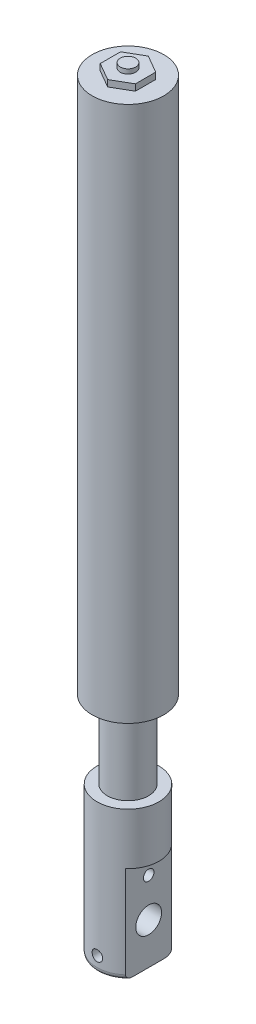
SolidWorks part; units mm, degrees
ref_plane "Piano frontale" through (0, 0, 0) normal (0, 0, 1) x (1, 0, 0)
ref_plane "Piano superiore" through (0, 0, 0) normal (0, 1, 0) x (1, 0, 0)
ref_plane "Piano destro" through (0, 0, 0) normal (1, 0, 0) x (0, 0, -1)
sketch "Schizzo1" plane through (0, 0, 0) normal (0, 1, 0) x (1, 0, 0)
  circle A0 centre (0, 0) radius 6.93
  dimension "D1" = 13.86
extrude "Estrusione-Estrusione1" add sketch "Schizzo1" along normal blind 103.85
sketch "Schizzo2" plane through (0, 103.85, 0) normal (0, 1, 0) x (1, 0, 0)
  line L1 (-3.4078, 1.9675) -> (-3.4078, -1.9675)
  line L2 (-3.4078, -1.9675) -> (0, -3.935)
  line L3 (0, -3.935) -> (3.4078, -1.9675)
  line L4 (3.4078, -1.9675) -> (3.4078, 1.9675)
  line L5 (3.4078, 1.9675) -> (0, 3.935)
  line L6 (0, 3.935) -> (-3.4078, 1.9675)
  circle A0 centre (0, 0) radius 3.935 construction
  dimension "D1" = 7.87
extrude "Estrusione-Estrusione2" add sketch "Schizzo2" along normal blind 1.24
sketch "Schizzo3" plane through (0, 105.09, 0) normal (0, 1, 0) x (1, 0, 0)
  circle A0 centre (0, 0) radius 1.495
  dimension "D1" = 2.99
extrude "Estrusione-Estrusione3" add sketch "Schizzo3" along normal blind 0.88
sketch "Schizzo4" plane through (0, 0, 0) normal (0, -1, 0) x (-1, 0, 0)
  circle A0 centre (0, 0) radius 3.995
  dimension "D1" = 7.99
extrude "Estrusione-Estrusione4" add sketch "Schizzo4" along normal blind 15.04
sketch "Schizzo5" plane through (0, -15.04, 0) normal (0, -1, 0) x (1, 0, 0)
  circle A0 centre (0, 0) radius 6
  dimension "D1" = 12
extrude "Estrusione-Estrusione5" add sketch "Schizzo5" along normal blind 28.8
sketch "Schizzo6" plane through (0, -43.84, 0) normal (0, -1, 0) x (1, 0, 0)
  line L0 (-4.01, 4.4632) -> (-4.01, -4.4632)
  line L1 (0, -6) -> (0, 6) construction
  line L2 (4.01, 4.4632) -> (4.01, -4.4632)
  circle A0 centre (0, 0) radius 6 construction
  circle A1 centre (0, 0) radius 6
  circle M1 centre (0, 0) radius 6
  dimension "D1" = 8.02
extrude "Taglio-Estrusione1" cut sketch "Schizzo6" against normal blind 18.82 contours L0 M1 | L2 M1
sketch "Schizzo7" plane through (-4.01, 0, 0) normal (-1, 0, 0) x (0, 0, 1)
  line L0 (0, -35.84) -> (0, -43.84) construction
  line L1 (4.4632, -43.84) -> (-4.4632, -43.84) construction
  circle A0 centre (0, -35.84) radius 2.5
  point P6 (0, -43.84)
  point P7 (0, -38.34)
  dimension "D1" = 5
  dimension "D2" = 5.5
extrude "Taglio-Estrusione2" cut sketch "Schizzo7" against normal through all
hole_wizard "Foro filettato M2.5x0.45-1" positions "Schizzo9" profile "Schizzo8" tap size "M2.5x0.45" standard "Ansi Metric" end condition through all
sketch "Schizzo9" plane through (-4.01, 0, 0) normal (-1, 0, 0) x (0, 0, 1)
  line L0 (0, -28.34) -> (0, -43.84) construction
  line L1 (4.4632, -43.84) -> (-4.4632, -43.84) construction
  point P0 (0, -28.34)
  dimension "D1" = 15.5
sketch "Schizzo8" plane through (-4.01, -28.34, 0) normal (0, 1, 0) x (0, 0, 1)
  line L0 (0, 0) -> (0, 10.94)
  line L1 (0, 10.94) -> (1.025, 10.94)
  line L2 (1.025, 10.94) -> (1.025, 0)
  line L5 (1.025, 0) -> (0, 0)
  line L11 (0, -6.35) -> (0, 107.95) construction
  dimension "Thread Major Dia." = 2.05
  dimension "Thru Tap Drill Depth" = 10.94
fillet "Raccordo1" radius 1 2 edges at (0, -43.84, 6) (0, -43.84, -6)
hole_wizard "Foro filettato M2.5x0.45-2" positions "Schizzo3D1" profile "Schizzo11" tap size "M2.5x0.45" standard "Ansi Metric" end condition through all
sketch3d "Schizzo3D1"
  line L0 (0, -43.84, 0) -> (0, -40.84, 0) construction
  line L1 (0, -41.5945, 0) -> (0, -46.8309, 0) construction
  line L3 (0, -40.84, 0) -> (0, -40.84, 6) construction
  point P0 (0, -40.84, 6)
  point P12 (0, -40.84, 6)
  dimension "D1" = 3
sketch "Schizzo11" plane through (0, -40.84, 6) normal (1, 0, 0) x (0, -1, 0)
  line L0 (0, 0) -> (0, 12.93)
  line L1 (0, 12.93) -> (1.025, 12.93)
  line L2 (1.025, 12.93) -> (1.025, 0)
  line L5 (1.025, 0) -> (0, 0)
  line L11 (0, -6.35) -> (0, 107.95) construction
  dimension "Thread Major Dia." = 2.05
  dimension "Thru Tap Drill Depth" = 12.93
ref_plane "Piano2" through (0, 0, -6) normal (0, 0, -1) x (-1, 0, 0)
sketch "Schizzo12" plane through (0, 0, -6) normal (0, 0, 1) x (1, 0, 0)
  circle A0 centre (0, -40.84) radius 2.5
  circle A1 centre (0, -40.84) radius 1.025 construction
  dimension "D1" = 5
extrude "Taglio-Estrusione5" cut sketch "Schizzo12" along normal blind 2.5
